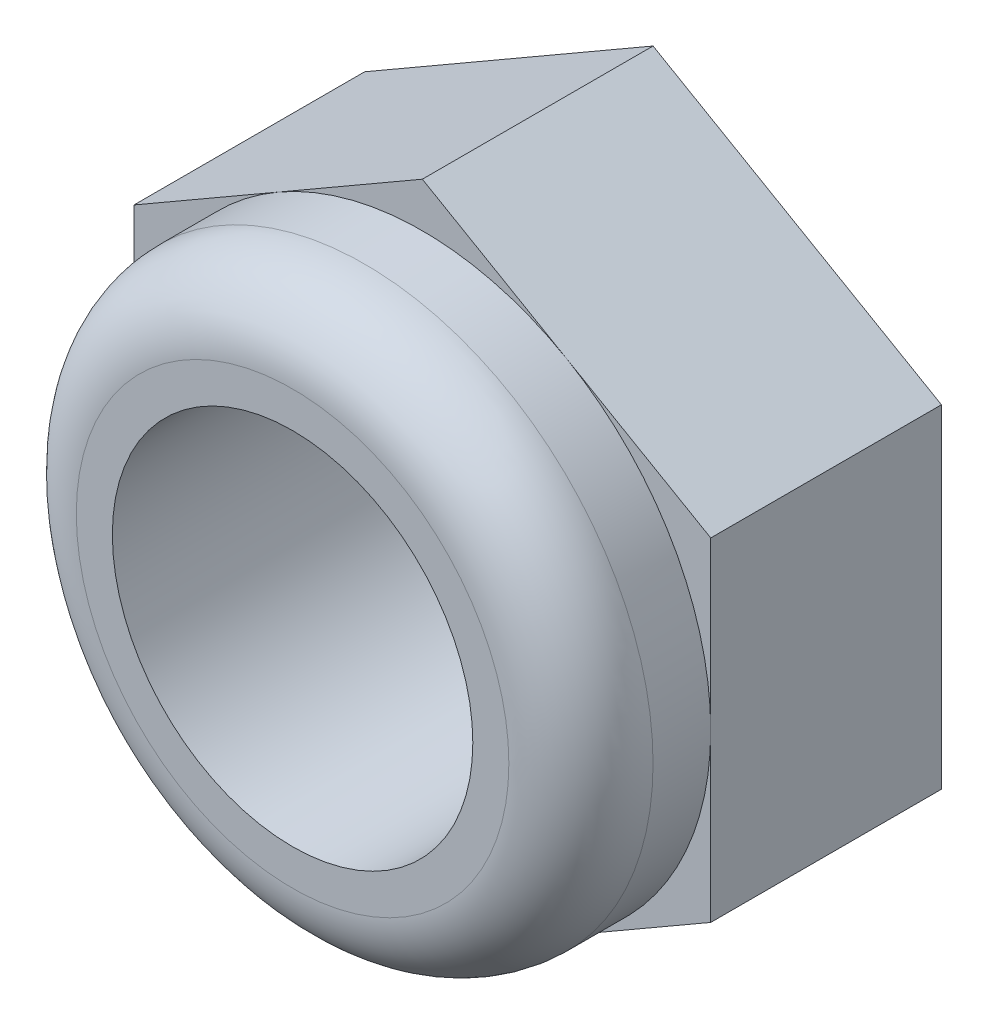
SolidWorks part; units mm, degrees
material "AISI 304"
ref_plane "Front Plane" through (0, 0, 0) normal (0, 0, 1) x (1, 0, 0)
ref_plane "Top Plane" through (0, 0, 0) normal (0, 1, 0) x (1, 0, 0)
ref_plane "Right Plane" through (0, 0, 0) normal (1, 0, 0) x (0, 0, -1)
sketch "草图1" plane through (0, 0, 0) normal (0, 0, 1) x (1, 0, 0)
  line L1 (4, -2.3094) -> (4, 2.3094)
  line L2 (4, 2.3094) -> (0, 4.6188)
  line L3 (0, 4.6188) -> (-4, 2.3094)
  line L4 (-4, 2.3094) -> (-4, -2.3094)
  line L5 (-4, -2.3094) -> (0, -4.6188)
  line L6 (0, -4.6188) -> (4, -2.3094)
  circle A0 centre (0, 0) radius 4 construction
  dimension "D1" = 8
extrude "凸台-拉伸1" add sketch "草图1" along normal blind 3.2
sketch "草图2" plane through (0, 0, 3.2) normal (0, 0, 1) x (1, 0, 0)
  line L0 (0, 4.6188) -> (-4, 2.3094) construction
  circle A0 centre (0, 0) radius 4
extrude "凸台-拉伸2" add sketch "草图2" along normal blind 1.8
sketch "草图3" plane through (0, 0, 5) normal (0, 0, 1) x (1, 0, 0)
  circle A0 centre (0, 0) radius 2.5
  dimension "D1" = 5
extrude "切除-拉伸1" cut sketch "草图3" against normal through all
fillet "圆角1" radius 1 1 edges at (4, 0, 5)
